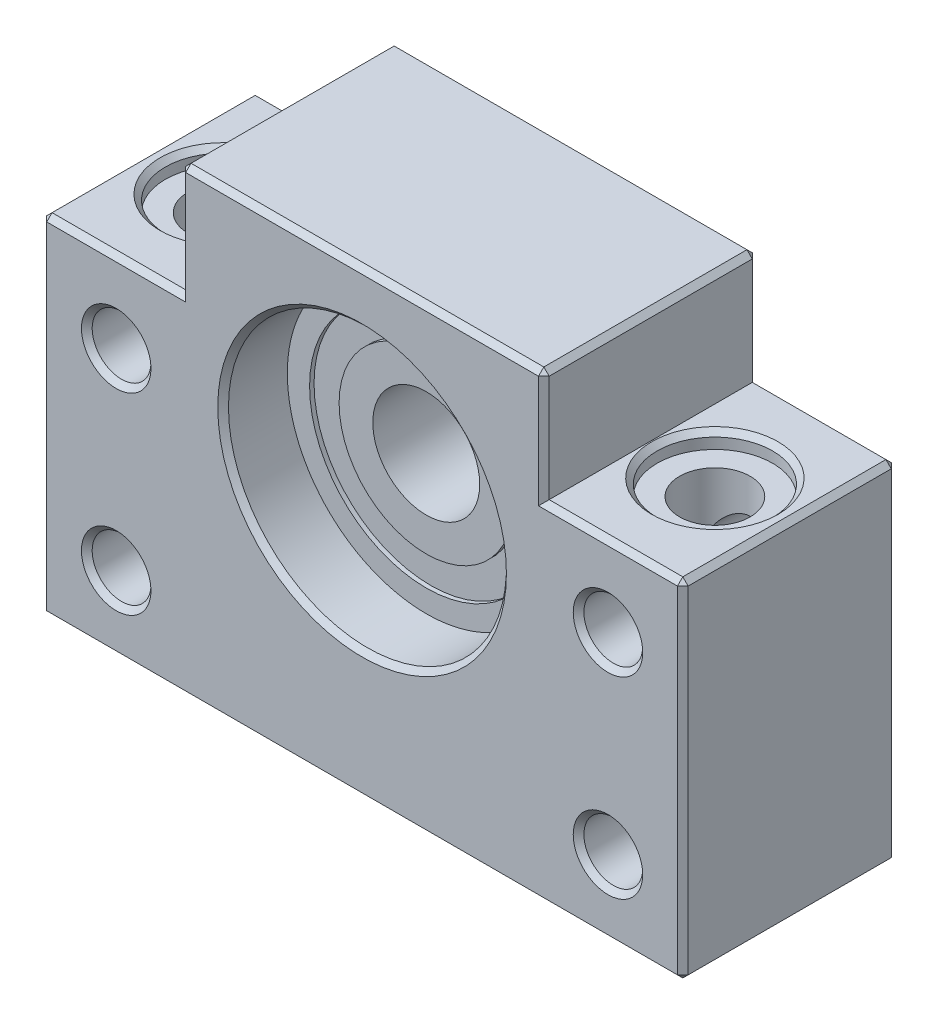
SolidWorks part; units mm, degrees
ref_plane "Front Plane" through (0, 0, 0) normal (0, 0, 1) x (1, 0, 0)
ref_plane "Top Plane" through (0, 0, 0) normal (0, 1, 0) x (1, 0, 0)
ref_plane "Right Plane" through (0, 0, 0) normal (1, 0, 0) x (0, 0, -1)
sketch "Sketch1" plane through (0, 0, 0) normal (0, 0, 1) x (1, 0, 0)
  line L0 (0, 25.0042) -> (0, -10.2914) construction
  line L1 (-27.5961, 0) -> (15.5514, 0) construction
  line L2 (17, 18) -> (-17, 18)
  line L3 (-17, 18) -> (-17, 7.5)
  line L4 (-17, 7.5) -> (-30, 7.5)
  line L5 (-30, 7.5) -> (-30, -25)
  line L6 (-30, -25) -> (30, -25)
  line L7 (30, 7.5) -> (30, -25)
  line L8 (17, 7.5) -> (30, 7.5)
  line L9 (17, 18) -> (17, 7.5)
  circle A0 centre (0, 0) radius 13
  point P14 (0, -25)
  point P17 (0, 18)
  dimension "D1" = 26
  dimension "D2" = 18
  dimension "D3" = 25
  dimension "D4" = 32.5
  dimension "D5" = 34
  dimension "D6" = 60
extrude "Boss-Extrude1" add sketch "Sketch1" along normal mid plane 20
sketch "Sketch2" plane through (0, 0, 10) normal (0, 0, 1) x (1, 0, 0)
  line L0 (-23, 0) -> (-23, -18) construction
  line L1 (0, 0) -> (0, -25) construction
  line L2 (-30, -25) -> (30, -25) construction
  circle A0 centre (-23, 0) radius 2.75
  circle A1 centre (-23, -18) radius 2.75
  circle A2 centre (23, -18) radius 2.75
  circle A3 centre (23, 0) radius 2.75
  dimension "D1" = 5.5
  dimension "D2" = 23
  dimension "D3" = 7
  dimension "D4" = 18
extrude "Cut-Extrude1" cut sketch "Sketch2" against normal through all
sketch "Sketch3" plane through (0, 7.5, 0) normal (0, 1, 0) x (1, 0, 0)
  line L0 (0, 0) -> (-23, 0) construction
  line L1 (0, 0) -> (0, 10) construction
  line L2 (17, 10) -> (-17, 10) construction
  circle A0 centre (-23, 0) radius 3.3
  circle A1 centre (23, 0) radius 3.3
  dimension "D1" = 6.6
  dimension "D2" = 23
extrude "Cut-Extrude2" cut sketch "Sketch3" against normal through all
sketch "Sketch4" plane through (0, 7.5, 0) normal (0, 1, 0) x (1, 0, 0)
  circle A0 centre (-23, 0) radius 5.4
  circle A1 centre (23, 0) radius 5.4
  dimension "D1" = 10.8
extrude "Cut-Extrude3" cut sketch "Sketch4" against normal blind 1.5
chamfer "Chamfer1" distance 0.5 angle 45 34 edges at (13, 0, -10) (-20.25, 0, -10) (20.25, 0, -10) (20.25, -18, -10) (-20.25, -18, -10) (13, 0, 10) (30, -25, 0) (30, 7.5, 0) (17, 18, 0) (-17, 18, 0) (-30, 7.5, 0) (-23.5, 7.5, -10) (-30, -8.75, -10) (-17, 12.75, -10) (0, 18, -10) (17, 12.75, -10) (23.5, 7.5, -10) (30, -8.75, -10) (0, -25, -10) (-30, -25, 0) (0, 18, 10) (17, 12.75, 10) (23.5, 7.5, 10) (30, -8.75, 10) (0, -25, 10) (-30, -8.75, 10) (-23.5, 7.5, 10) (-17, 12.75, 10) (-20.25, 0, 10) (20.25, 0, 10) (20.25, -18, 10) (-20.25, -18, 10) (17.6, 7.5, 0) (-28.4, 7.5, 0)
sketch "Sketch5" plane through (0, 0, 0) normal (0, 1, 0) x (1, 0, 0)
  line L1 (-13, 4) -> (-10.9114, 4)
  line L2 (-13, 4) -> (-13, 0)
  line L3 (-13, 0) -> (-5, 0)
  line L4 (-5, 4) -> (-5, 0)
  line L5 (0, 0) -> (-5, 0) construction
  line L6 (-16.5, 10) -> (16.5, 10) construction
  line L7 (-8.1511, 4) -> (-5, 4)
  line L8 (0, 0) -> (0, 10) construction
  line L9 (-10.9114, 4) -> (-10.9114, 3.5824)
  line L10 (-10.9114, 3.5824) -> (-8.1511, 3.5824)
  line L11 (-8.1511, 4) -> (-8.1511, 3.5824)
  line L12 (-13, 9.5) -> (-13, -9.5) construction
  point P14 (0, 0)
  dimension "D1" = 5
  dimension "D2" = 6
revolve "Revolve1" add sketch "Sketch5" angle 360 about L8
mirror "Mirror2" about plane through (-13, 0, 0) normal (0, 0, -1) of bodies 105
